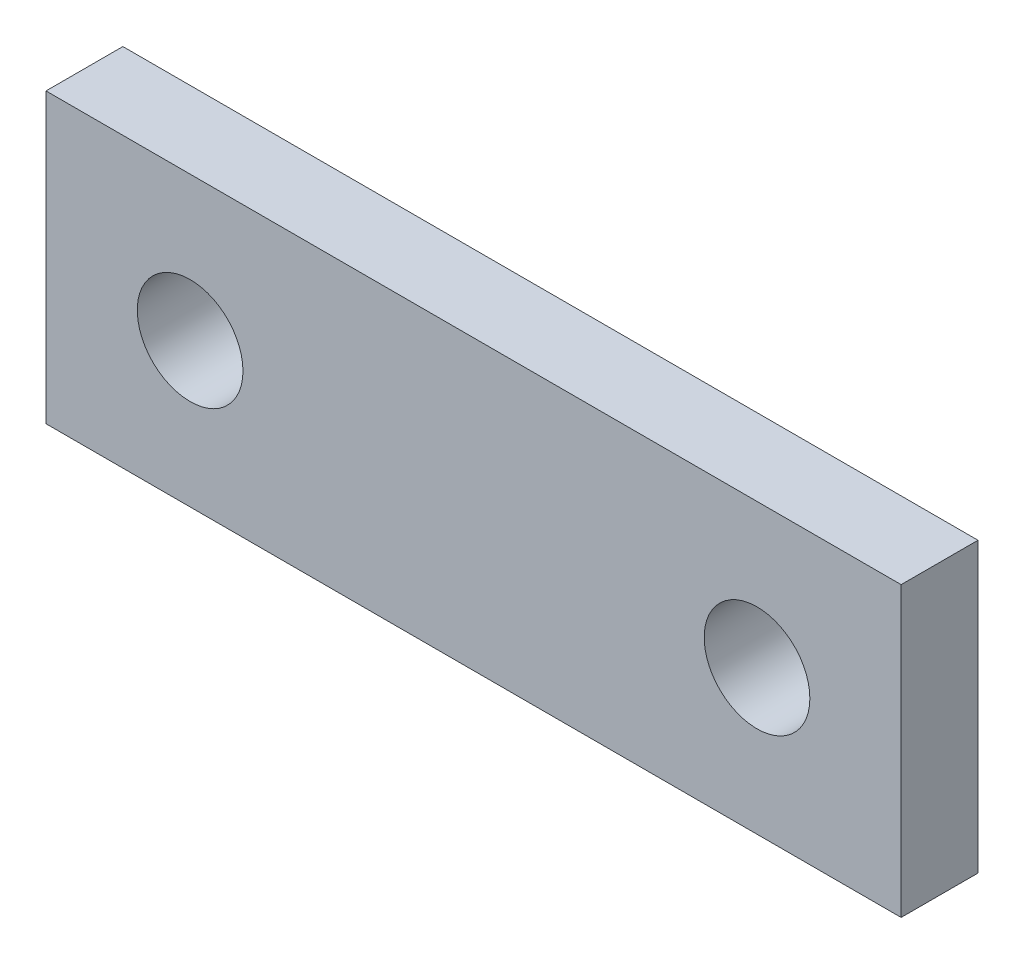
SolidWorks part; units mm, degrees
ref_plane "前视基准面" through (0, 0, 0) normal (0, 0, 1) x (1, 0, 0)
ref_plane "上视基准面" through (0, 0, 0) normal (0, 1, 0) x (1, 0, 0)
ref_plane "右视基准面" through (0, 0, 0) normal (1, 0, 0) x (0, 0, -1)
sketch "草图1" plane through (0, 0, 0) normal (0, 0, 1) x (1, 0, 0)
  line L1 (0, 0) -> (178, 0)
  line L2 (0, 0) -> (0, 60)
  line L3 (0, 60) -> (178, 60)
  line L4 (178, 0) -> (178, 60)
  dimension "D1" = 178
  dimension "D2" = 60
extrude "拉伸1" add sketch "草图1" along normal blind 16
sketch "草图2" plane through (0, 0, 16) normal (0, 0, 1) x (1, 0, 0)
  line L0 (0, 30) -> (178, 30) construction
  line L1 (0, 60) -> (0, 0) construction
  line L2 (178, 0) -> (178, 60) construction
  line L3 (89, 60) -> (89, 0) construction
  line L4 (178, 60) -> (0, 60) construction
  line L5 (0, 0) -> (178, 0) construction
  circle A0 centre (30, 30) radius 11
  circle A1 centre (148, 30) radius 11
  dimension "D3" = 22
  dimension "D1" = 59
  dimension "D2" = 118
extrude "拉伸2" cut sketch "草图2" against normal through all
